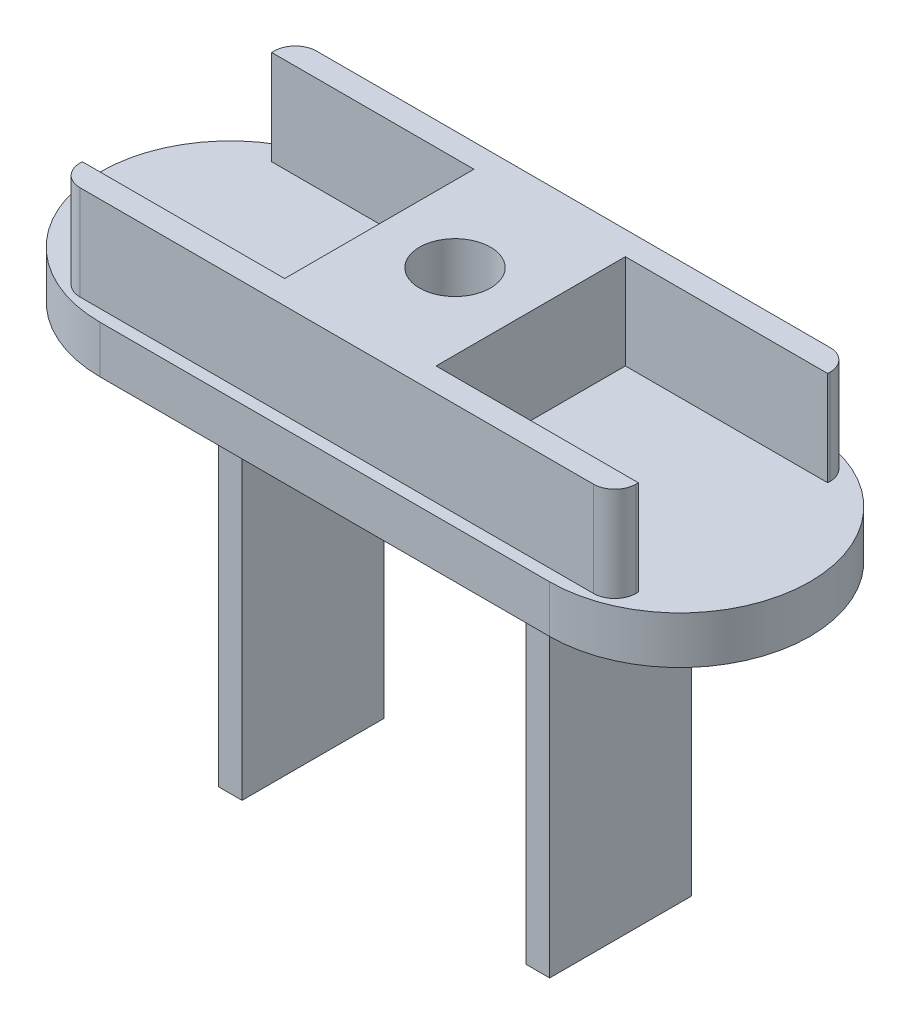
SolidWorks part; units mm, degrees
ref_plane "Alzado" through (0, 0, 0) normal (0, 0, 1) x (1, 0, 0)
ref_plane "Planta" through (0, 0, 0) normal (0, 1, 0) x (1, 0, 0)
ref_plane "Vista lateral" through (0, 0, 0) normal (1, 0, 0) x (0, 0, -1)
sketch "Croquis1" plane through (0, 0, 0) normal (0, 1, 0) x (1, 0, 0)
  line L0 (-9.5, 0) -> (9.5, 0) construction
  line L1 (-9.5, 5.5) -> (9.5, 5.5)
  line L2 (-9.5, -5.5) -> (9.5, -5.5)
  line L3 (-15, 0) -> (15, 0) construction
  arc A0 (-9.5, 5.5) -> (-9.5, -5.5) centre (-9.5, 0) ccw
  arc A1 (9.5, -5.5) -> (9.5, 5.5) centre (9.5, 0) ccw
  point P3 (0, 0)
  dimension "D1" = 11
  dimension "D2" = 30
extrude "Saliente-Extruir1" add sketch "Croquis1" along normal blind 2
sketch "Croquis2" plane through (0, 2, 0) normal (0, 1, 0) x (1, 0, 0)
  line L0 (-3.2, 4) -> (-3.2, -4)
  line L1 (-3.2, -4) -> (-11.75, -4)
  line L2 (-11.75, -4) -> (-11.75, -4.1)
  line L3 (-10.85, -5) -> (10.85, -5)
  line L4 (11.75, -4.1) -> (11.75, -4)
  line L5 (11.75, -4) -> (3.2, -4)
  line L6 (3.2, -4) -> (3.2, 4)
  line L7 (3.2, 4) -> (11.75, 4)
  line L8 (11.75, 4) -> (11.75, 4.1)
  line L9 (10.85, 5) -> (-10.85, 5)
  line L10 (-11.75, 4.1) -> (-11.75, 4)
  line L11 (-11.75, 4) -> (-3.2, 4)
  arc A0 (-11.75, -4.1) -> (-10.85, -5) centre (-10.85, -4.1) ccw
  arc A1 (10.85, -5) -> (11.75, -4.1) centre (10.85, -4.1) ccw
  arc A2 (11.75, 4.1) -> (10.85, 5) centre (10.85, 4.1) ccw
  arc A3 (-10.85, 5) -> (-11.75, 4.1) centre (-10.85, 4.1) ccw
  point P9 (0, 5)
  point P13 (3.2, 0)
  point P21 (11.75, 5)
  point P24 (-11.75, 5)
  dimension "D5" = 0.9
  dimension "D1" = 10
  dimension "D2" = 6.4
  dimension "D3" = 23.5
  dimension "D4" = 1
extrude "Saliente-Extruir2" add sketch "Croquis2" along normal blind 4
sketch "Croquis3" plane through (0, 6, 0) normal (0, 1, 0) x (1, 0, 0)
  circle A0 centre (0, 0) radius 1.5
  dimension "D1" = 3
extrude "Cortar-Extruir1" cut sketch "Croquis3" against normal up to next
sketch "Croquis4" plane through (0, 0, 0) normal (0, -1, 0) x (1, 0, 0)
  line L0 (-6, 0) -> (6, 0) construction
  line L1 (-7, 3) -> (-6, 3)
  line L2 (-7, 3) -> (-7, -3)
  line L3 (-7, -3) -> (-6, -3)
  line L4 (-6, 3) -> (-6, -3)
  line L5 (6, 3) -> (7, 3)
  line L6 (6, 3) -> (6, -3)
  line L7 (6, -3) -> (7, -3)
  line L8 (7, 3) -> (7, -3)
  point P10 (0, 0)
  dimension "D1" = 14
  dimension "D2" = 1
  dimension "D3" = 6
extrude "Saliente-Extruir3" add sketch "Croquis4" along normal blind 15
